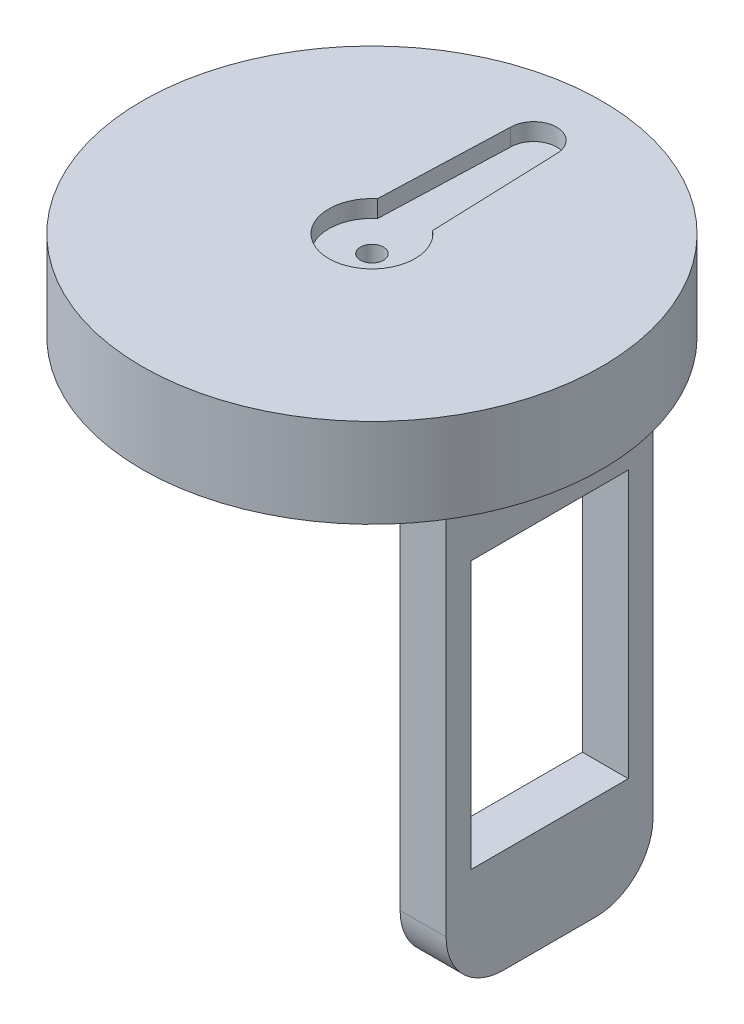
SolidWorks part; units mm, degrees
ref_plane "Front Plane" through (0, 0, 0) normal (0, 0, 1) x (1, 0, 0)
ref_plane "Top Plane" through (0, 0, 0) normal (0, 1, 0) x (1, 0, 0)
ref_plane "Right Plane" through (0, 0, 0) normal (1, 0, 0) x (0, 0, -1)
sketch "Sketch1" plane through (0, 0, 0) normal (0, 1, 0) x (1, 0, 0)
  circle A0 centre (0, 0) radius 20
  circle A1 centre (0, 0) radius 18
  dimension "D1" = 40
  dimension "D2" = 2
extrude "Boss-Extrude1" add sketch "Sketch1" along normal blind 7.75
sketch "Sketch2" plane through (0, 7.75, 0) normal (0, 1, 0) x (1, 0, 0)
  circle A0 centre (0, 0) radius 18
extrude "Boss-Extrude2" add sketch "Sketch2" against normal blind 4
sketch "Sketch3" plane through (0, 7.75, 0) normal (0, 1, 0) x (1, 0, 0)
  line L0 (-2.4, 2.8814) -> (-2, 14.0643)
  line L5 (-2, 14.0643) -> (2, 14.0643) construction
  line L6 (2, 14.0643) -> (2.4, 2.8814)
  arc A0 (-2.4, 2.8814) -> (2.4, 2.8814) centre (0, 0) ccw
  arc A1 (-2, 14.0643) -> (2, 14.0643) centre (0, 14.0643) cw
  point P0 (0, 0)
  point P13 (2, 14.4833)
  dimension "D1" = 7.5
  dimension "D3" = 2
  dimension "D4" = 11.19
  dimension "D2" = 4.8
extrude "Cut-Extrude1" cut sketch "Sketch3" against normal blind 1.5
sketch "Sketch4" plane through (0, 6.25, 0) normal (0, 1, 0) x (1, 0, 0)
  circle A0 centre (0, 0) radius 1
  dimension "D1" = 2
extrude "Cut-Extrude2" cut sketch "Sketch4" against normal blind 1.5
ref_plane "Plane1" through (11.45, 0, 0) normal (1, 0, 0) x (0, 0, -1)
sketch "Sketch5" plane through (11.45, 0, 0) normal (1, 0, 0) x (0, 0, -1)
  line L0 (-20, 0) -> (20, 0) construction
  line L1 (-9, 0) -> (9, 0)
  line L2 (-9, 0) -> (-9, -38)
  line L3 (-9, -38) -> (9, -38)
  line L4 (9, 0) -> (9, -38)
  line L5 (0, 0) -> (0, -48.4122) construction
  line L7 (-6.85, -5.75) -> (6.85, -5.75)
  line L8 (-6.85, -5.75) -> (-6.85, -29)
  line L9 (-6.85, -29) -> (6.85, -29)
  line L10 (6.85, -5.75) -> (6.85, -29)
  point P13 (0, -5.75)
  dimension "D1" = 38
  dimension "D2" = 18
  dimension "D3" = 9
  dimension "D4" = 5.75
  dimension "D5" = 13.7
  dimension "D6" = 23.25
extrude "Boss-Extrude3" add sketch "Sketch5" along normal blind 4 separate body
sketch "Sketch6" plane through (0, 0, 0) normal (0, -1, 0) x (1, 0, 0)
  circle A0 centre (0, 0) radius 18
extrude "Boss-Extrude4" add sketch "Sketch6" against normal blind 2
sketch "Sketch7" plane through (11.45, 0, 0) normal (-1, 0, 0) x (0, 0, 1)
  line L0 (6.85, -29) -> (-6.85, -29) construction
  line L1 (-6.85, -5.75) -> (6.85, -5.75) construction
  circle A0 centre (0, -30.85) radius 0.5
  circle A1 centre (0, -3.25) radius 0.5
  dimension "D2" = 1
  dimension "D3" = 1
  dimension "D1" = 1.85
  dimension "D4" = 2.5
extrude "Cut-Extrude3" cut sketch "Sketch7" against normal blind 3
fillet "Fillet1" radius 5 2 edges at (13.45, -38, -9) (13.45, -38, 9)
